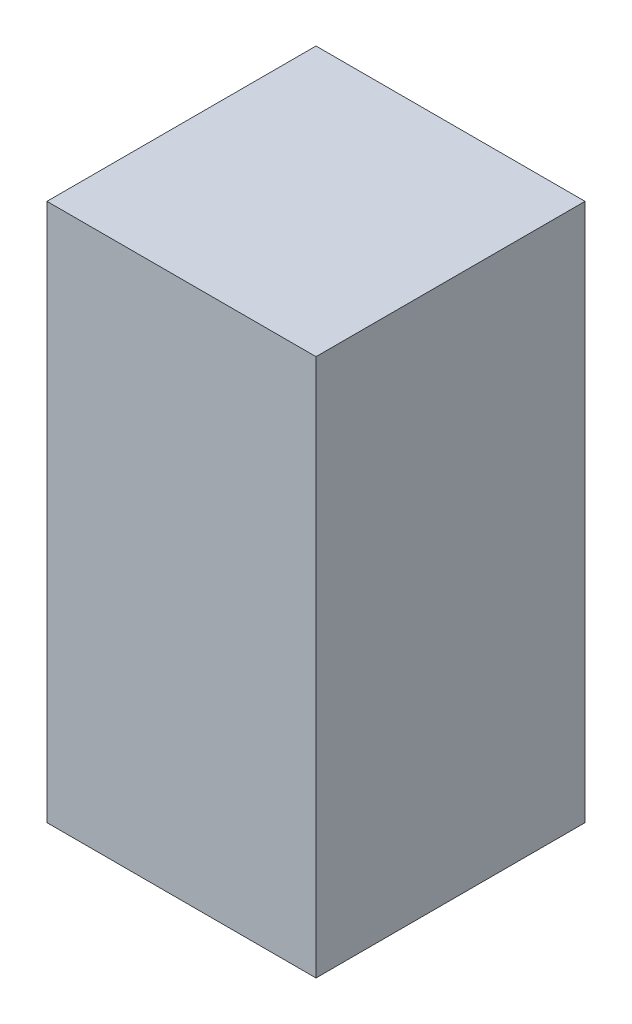
SolidWorks part; units mm, degrees
material "ABS"
ref_plane "Front Plane" through (0, 0, 0) normal (0, 0, 1) x (1, 0, 0)
ref_plane "Top Plane" through (0, 0, 0) normal (0, 1, 0) x (1, 0, 0)
ref_plane "Right Plane" through (0, 0, 0) normal (1, 0, 0) x (0, 0, -1)
sketch "Sketch1" plane through (0, 0, 0) normal (0, 1, 0) x (1, 0, 0)
  line L1 (0, 0) -> (50, 0)
  line L2 (0, 0) -> (0, 50)
  line L3 (0, 50) -> (50, 50)
  line L4 (50, 0) -> (50, 50)
  dimension "D1" = 50
  dimension "D2" = 50
extrude "Boss-Extrude1" add sketch "Sketch1" along normal blind 100
sketch3d "URDF Reference"
  line L0 (0, 0, 0) -> (10, 0, 0) construction
  line L1 (0, 0, 0) -> (0, 0, -10) construction
  point P0 (0, 0, 0)
  point P1 (0, 0, 0)
